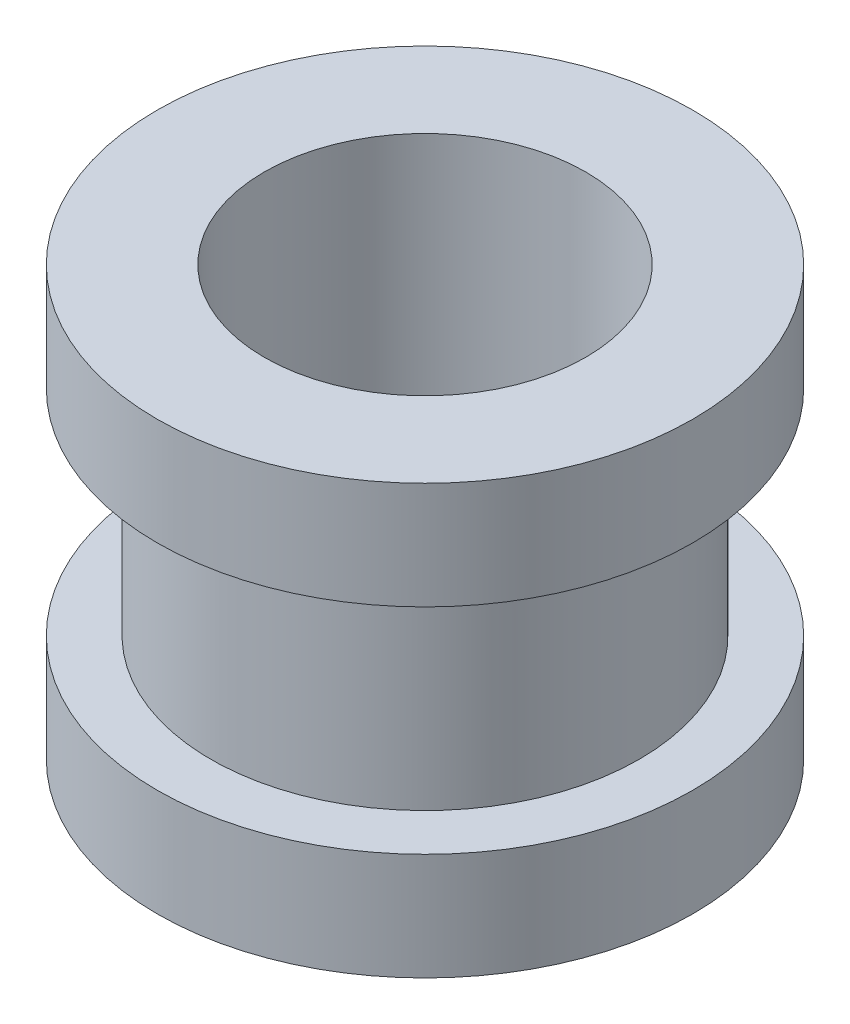
SolidWorks part; units mm, degrees
ref_plane "Front Plane" through (0, 0, 0) normal (0, 0, 1) x (1, 0, 0)
ref_plane "Top Plane" through (0, 0, 0) normal (0, 1, 0) x (1, 0, 0)
ref_plane "Right Plane" through (0, 0, 0) normal (1, 0, 0) x (0, 0, -1)
sketch "Sketch1" plane through (0, 0, 0) normal (0, 0, 1) x (1, 0, 0)
  line L0 (0, 2) -> (0, 0)
  line L1 (0, 2) -> (-2.5, 2)
  line L2 (-2.5, 2) -> (-2.5, 1)
  line L3 (-2.5, 1) -> (-2, 1)
  line L4 (-2, 1) -> (-2, 0)
  line L8 (-2, 0) -> (0, 0)
  dimension "D1" = 2
  dimension "D2" = 1
  dimension "D3" = 2
  dimension "D4" = 2.5
revolve "Revolve1" add sketch "Sketch1" angle 360 about L0
mirror "Mirror1" about plane through (-2, 0, 0) normal (0, -1, 0) of "Revolve1"
sketch "Sketch2" plane through (0, 2, 0) normal (0, 1, 0) x (1, 0, 0)
  circle A0 centre (0, 0) radius 1.5
  dimension "D1" = 3
extrude "Cut-Extrude1" cut sketch "Sketch2" against normal through all
